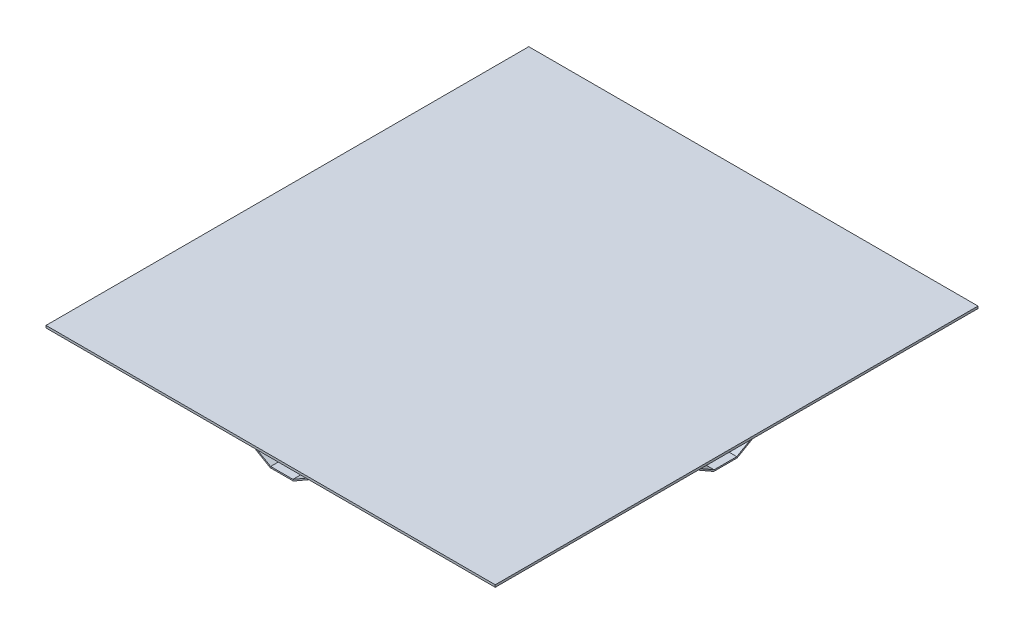
SolidWorks part; units mm, degrees
material "AISI 1020"
ref_plane "Спереди" through (0, 0, 0) normal (0, 0, 1) x (1, 0, 0)
ref_plane "Сверху" through (0, 0, 0) normal (0, 1, 0) x (1, 0, 0)
ref_plane "Справа" through (0, 0, 0) normal (1, 0, 0) x (0, 0, -1)
sketch "Эскиз1" plane through (0, 0, 0) normal (0, 1, 0) x (1, 0, 0)
  line L1 (502.5, -540) -> (-502.5, -540)
  line L2 (502.5, -540) -> (502.5, 540)
  line L3 (502.5, 540) -> (-502.5, 540)
  line L4 (-502.5, -540) -> (-502.5, 540)
  line L5 (502.5, -540) -> (-502.5, 540) construction
  line L6 (502.5, 540) -> (-502.5, -540) construction
  point P0 (0, 0)
  dimension "D1" = 1005
  dimension "D2" = 1080
extrude "Бобышка-Вытянуть1" add sketch "Эскиз1" along normal blind 3
sketch "Эскиз2" plane through (0, 0, 0) normal (0, 0, 1) x (1, 0, 0)
  line L0 (0, -1000) -> (0, 49000) construction
  line L1 (25, -44) -> (-25, -44)
  line L2 (-25, -44) -> (-101.2102, 0)
  line L3 (-502.5, 0) -> (502.5, 0) construction
  line L4 (25, -44) -> (101.2102, 0)
  line L5 (-101.2102, 0) -> (-152.0141, 0)
  line L6 (101.2102, 0) -> (152.0141, 0)
  line L7 (-152.0141, 0) -> (-152.0141, -3)
  line L8 (152.0141, 0) -> (152.0141, -3)
  line L9 (-152.0141, -3) -> (-102.0141, -3)
  line L10 (152.0141, -3) -> (102.0141, -3)
  line L11 (-102.0141, -3) -> (-25.8038, -47)
  line L12 (102.0141, -3) -> (25.8038, -47)
  line L13 (-25.8038, -47) -> (25.8038, -47)
  line L14 (-502.5, 3) -> (502.5, 3) construction
  point P6 (0, -44)
  point P18 (0, -47)
  dimension "D1" = 3
  dimension "D2" = 3
  dimension "D3" = 3
  dimension "D4" = 30
  dimension "D5" = 50
  dimension "D6" = 50
extrude "Бобышка-Вытянуть2" add sketch "Эскиз2" along normal offset from surface 25 and the other way offset from surface (515 mm away) 25 up to face at (0, 1.5, 540) other way up to face at (0, 1.5, -540)
sketch "Эскиз3" plane through (0, 0, 0) normal (1, 0, 0) x (0, 0, -1)
  line L0 (0, -1000) -> (0, 49000) construction
  line L1 (-26.2058, -47) -> (26.2058, -47)
  line L2 (26.2058, -47) -> (102.416, -3)
  line L3 (-26.2058, -47) -> (-102.416, -3)
  line L4 (102.416, -3) -> (152.416, -3)
  line L5 (-102.416, -3) -> (-152.416, -3)
  line L6 (152.416, -3) -> (152.416, 0)
  line L7 (-152.416, -3) -> (-152.416, 0)
  line L8 (152.416, 0) -> (101.6122, 0)
  line L9 (-152.416, 0) -> (-101.6122, 0)
  line L10 (101.6122, 0) -> (25.4019, -44)
  line L11 (-101.6122, 0) -> (-25.4019, -44)
  line L12 (25.4019, -44) -> (-25.4019, -44)
  line L13 (-540, 0) -> (540, 0) construction
  line L14 (-515, -47) -> (515, -47) construction
  line L15 (-515, 0) -> (515, 0) construction
  point P6 (0, -47)
  point P16 (0, -44)
  point P17 (-66.2145, -19.5488)
  dimension "D1" = 3
  dimension "D2" = 3
  dimension "D3" = 3
  dimension "D4" = 50
  dimension "D5" = 30
extrude "Бобышка-Вытянуть3" add sketch "Эскиз3" along normal offset from surface 25 and the other way offset from surface (477.5 mm away) 25 up to face at (502.5, 1.5, 0) other way up to face at (-502.5, 1.5, 0)
sketch "Эскиз4" plane through (-502.5, 0, 0) normal (-1, 0, 0) x (0, 0, 1)
  line L4 (-540, 0) -> (540, 0)
  line L5 (540, 0) -> (540, 3)
  line L6 (540, 3) -> (-540, 3)
  line L7 (-540, 3) -> (-540, 0)
  line L8 (-540, 0) -> (540, 0)
  line L9 (540, 0) -> (540, 3)
  line L10 (540, 3) -> (-540, 3)
  line L11 (-540, 3) -> (-540, 0)
  dimension "D1" = 0
sketch "Эскиз5" plane through (0, 0, 0) normal (0, -1, 0) x (1, 0, 0)
  line L0 (502.5, -540) -> (-502.5, -540) construction
  line L1 (-502.5, 540) -> (-502.5, -540) construction
  line L2 (502.5, 540) -> (502.5, -540) construction
  line L3 (-502.5, 540) -> (502.5, 540) construction
  line L4 (502.5, -540) -> (-502.5, -540)
  line L5 (-502.5, 540) -> (-502.5, -540)
  line L6 (502.5, 540) -> (502.5, -540)
  line L7 (-502.5, 540) -> (502.5, 540)
  line L8 (-487.5, 525) -> (-487.5, -525)
  line L9 (487.5, -525) -> (-487.5, -525)
  line L10 (487.5, 525) -> (487.5, -525)
  line L11 (-487.5, 525) -> (487.5, 525)
  dimension "D1" = 15
extrude "Бобышка-Вытянуть5" add sketch "Эскиз5" along normal blind 2
